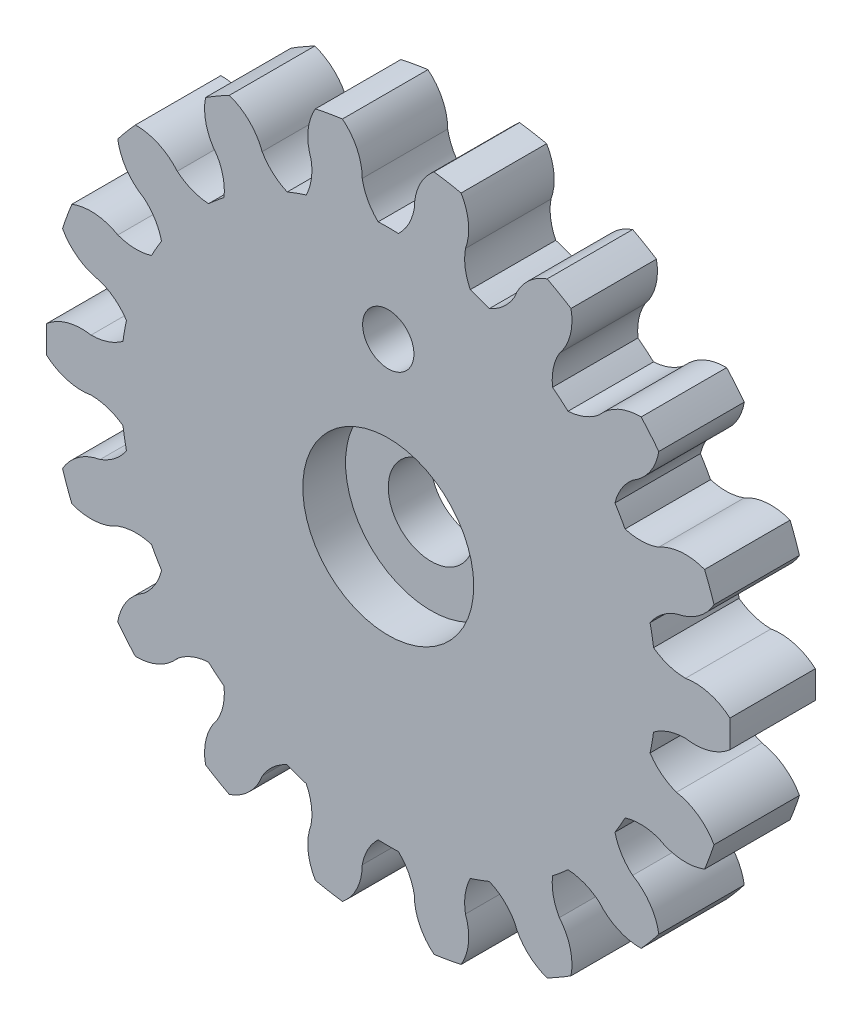
SolidWorks part; units mm, degrees
ref_plane "Alzado" through (0, 0, 0) normal (0, 0, 1) x (1, 0, 0)
ref_plane "Planta" through (0, 0, 0) normal (0, 1, 0) x (1, 0, 0)
ref_plane "Vista lateral" through (0, 0, 0) normal (1, 0, 0) x (0, 0, -1)
sketch "Croquis1" plane through (0, 0, 0) normal (0, 0, 1) x (1, 0, 0)
  circle A0 centre (0, 0) radius 20
  circle A1 centre (0, 0) radius 2.5
  circle A2 centre (0, 10) radius 1.5
  dimension "D1" = 40
  dimension "D2" = 5
  dimension "D4" = 3
  dimension "D3" = 10
extrude "Saliente-Extruir1" add sketch "Croquis1" along normal blind 5
sketch "Croquis2" plane through (0, 0, 5) normal (0, 0, 1) x (1, 0, 0)
  line L0 (0, 0) -> (0, 21.6776) construction
  arc A0 (2.6786, 19.8198) -> (-2.6786, 19.8198) centre (0, 0) ccw
  arc A1 (0.5915, 15.6538) -> (-0.5915, 15.6538) centre (0, 0) ccw
  arc A2 (1.57, 17.9314) -> (-1.57, 17.9314) centre (0, 0) ccw construction
  arc A3 (-1.5222, 17.3857) -> (-2.6786, 19.8198) centre (-4.6622, 17.3857) ccw
  arc A5 (-1.5222, 17.3857) -> (-0.5915, 15.6538) centre (1.57, 17.9314) ccw
  arc A6 (2.6786, 19.8198) -> (1.5222, 17.3857) centre (4.6622, 17.3857) ccw
  arc A7 (0.5915, 15.6538) -> (1.5222, 17.3857) centre (-1.57, 17.9314) ccw
  dimension "D1" = 31.33
  dimension "D2" = 36
  dimension "D3" = 6.28
  dimension "D4" = 1.57
extrude "Cortar-Extruir1" cut sketch "Croquis2" against normal through all
pattern_circular "MatrizC1" count 18 over 360 about axis through (0, 0, 0) along (0, 0, 1) of "Cortar-Extruir1"
sketch "Croquis3" plane through (0, 0, 5) normal (0, 0, 1) x (1, 0, 0)
  circle A0 centre (0, 0) radius 5
  dimension "D1" = 10
extrude "Cortar-Extruir2" cut sketch "Croquis3" against normal blind 2.5
